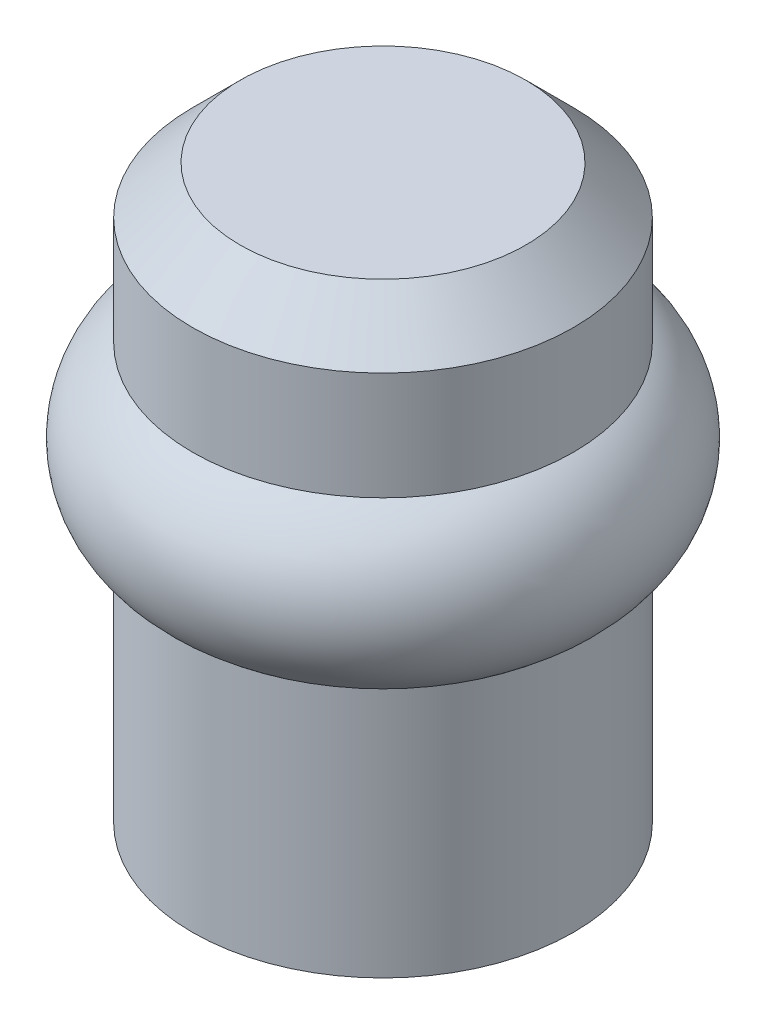
SolidWorks part; units mm, degrees
ref_plane "Front Plane" through (0, 0, 0) normal (0, 0, 1) x (1, 0, 0)
ref_plane "Top Plane" through (0, 0, 0) normal (0, 1, 0) x (1, 0, 0)
ref_plane "Right Plane" through (0, 0, 0) normal (1, 0, 0) x (0, 0, -1)
sketch "Sketch1" plane through (0, 0, 0) normal (0, 0, 1) x (1, 0, 0)
  line L0 (0, 0) -> (0, 77.5312) construction
  line L1 (0, 0) -> (-25.4, 0)
  line L2 (-25.4, 0) -> (-25.4, 33.4515)
  line L3 (0, 76.2) -> (-19.05, 76.2)
  line L4 (-19.05, 76.2) -> (-25.4, 69.85)
  line L5 (-25.4, 69.85) -> (-25.4, 55.4485)
  line L6 (0, 76.2) -> (0, 0)
  arc A0 (-25.4, 55.4485) -> (-25.4, 33.4515) centre (-19.05, 44.45) ccw
  point P5 (-31.75, 44.45)
  dimension "D4" = 12.7
  dimension "D5" = 6.35
  dimension "D7" = 63.5
  dimension "D1" = 44.45
  dimension "D2" = 76.2
  dimension "D3" = 6.35
  dimension "D6" = 50.8
revolve "Revolve1" add sketch "Sketch1" angle 360 about L0
